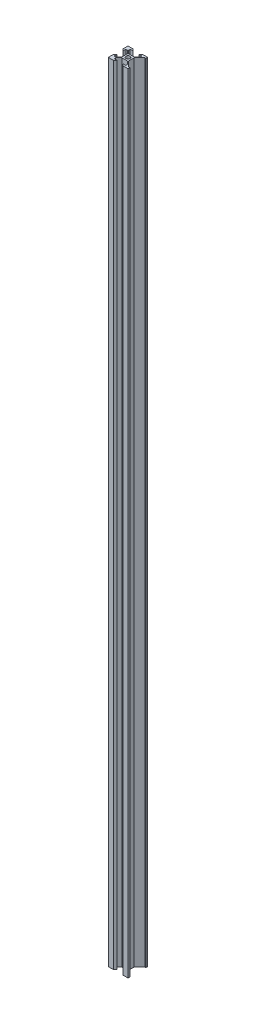
SolidWorks part; units mm, degrees
ref_plane "前视基准面" through (0, 0, 0) normal (0, 0, 1) x (1, 0, 0)
ref_plane "上视基准面" through (0, 0, 0) normal (0, 1, 0) x (1, 0, 0)
ref_plane "右视基准面" through (0, 0, 0) normal (1, 0, 0) x (0, 0, -1)
sketch "草图1" plane through (0, 0, 0) normal (0, 1, 0) x (1, 0, 0)
  line L0 (-25.721, 0) -> (73.7722, 0)
  line L1 (0, 21.255) -> (0, -16.6235)
  line L2 (-10, 21.255) -> (-10, -16.6235)
  line L3 (-25.721, 10) -> (73.7722, 10)
  line L4 (-4.9, 10) -> (-3.1, 8.2)
  line L5 (-3.1, 8.2) -> (-5.9236, 8.2)
  line L6 (-5.9236, 8.2) -> (-5.9236, 6.56)
  line L7 (-5.9236, 6.56) -> (-2.84, 3.4764)
  line L8 (-2.84, 3.4764) -> (2.84, 3.4764)
  line L9 (-10, 10) -> (0, 0) construction
  line L10 (5.9236, 6.56) -> (2.84, 3.4764)
  line L11 (5.9236, 8.2) -> (5.9236, 6.56)
  line L12 (3.1, 8.2) -> (5.9236, 8.2)
  line L13 (4.9, 10) -> (3.1, 8.2)
  line L14 (-10, -4.9) -> (-8.2, -3.1)
  line L15 (-8.2, -3.1) -> (-8.2, -5.9236)
  line L16 (-8.2, -5.9236) -> (-6.56, -5.9236)
  line L17 (-6.56, -5.9236) -> (-3.4764, -2.84)
  line L18 (-3.4764, 2.84) -> (-3.4764, -2.84)
  line L19 (-6.56, 5.9236) -> (-3.4764, 2.84)
  line L20 (-8.2, 5.9236) -> (-6.56, 5.9236)
  line L21 (-8.2, 3.1) -> (-8.2, 5.9236)
  line L22 (-10, 4.9) -> (-8.2, 3.1)
  line L23 (-25.721, -10) -> (73.7722, -10)
  line L24 (4.9, -10) -> (3.1, -8.2)
  line L25 (3.1, -8.2) -> (5.9236, -8.2)
  line L26 (5.9236, -8.2) -> (5.9236, -6.56)
  line L27 (5.9236, -6.56) -> (2.84, -3.4764)
  line L28 (-2.84, -3.4764) -> (2.84, -3.4764)
  line L29 (-5.9236, -6.56) -> (-2.84, -3.4764)
  line L30 (-5.9236, -8.2) -> (-5.9236, -6.56)
  line L31 (-3.1, -8.2) -> (-5.9236, -8.2)
  line L32 (-4.9, -10) -> (-3.1, -8.2)
  line L33 (50, 21.255) -> (50, -16.6235)
  line L34 (20, 21.255) -> (20, -16.6235)
  line L35 (10, 4.9) -> (8.2, 3.1)
  line L36 (8.2, 3.1) -> (8.2, 5.9236)
  line L37 (8.2, 5.9236) -> (6.56, 5.9236)
  line L38 (6.56, 5.9236) -> (3.4764, 2.84)
  line L39 (3.4764, 2.84) -> (3.4764, -2.84)
  line L40 (6.56, -5.9236) -> (3.4764, -2.84)
  line L41 (8.2, -5.9236) -> (6.56, -5.9236)
  line L42 (8.2, -3.1) -> (8.2, -5.9236)
  line L43 (10, -4.9) -> (8.2, -3.1)
  line L44 (15.1, 10) -> (16.9, 8.2)
  line L45 (16.9, 8.2) -> (14.0764, 8.2)
  line L46 (14.0764, 8.2) -> (14.0764, 6.56)
  line L47 (14.0764, 6.56) -> (17.16, 3.4764)
  line L48 (17.16, 3.4764) -> (22.84, 3.4764)
  line L49 (25.9236, 6.56) -> (22.84, 3.4764)
  line L50 (25.9236, 8.2) -> (25.9236, 6.56)
  line L51 (23.1, 8.2) -> (25.9236, 8.2)
  line L52 (24.9, 10) -> (23.1, 8.2)
  line L53 (10, -4.9) -> (11.8, -3.1)
  line L54 (11.8, -3.1) -> (11.8, -5.9236)
  line L55 (11.8, -5.9236) -> (13.44, -5.9236)
  line L56 (13.44, -5.9236) -> (16.5236, -2.84)
  line L57 (16.5236, 2.84) -> (16.5236, -2.84)
  line L58 (13.44, 5.9236) -> (16.5236, 2.84)
  line L59 (11.8, 5.9236) -> (13.44, 5.9236)
  line L60 (11.8, 3.1) -> (11.8, 5.9236)
  line L61 (10, 4.9) -> (11.8, 3.1)
  line L62 (24.9, -10) -> (23.1, -8.2)
  line L63 (23.1, -8.2) -> (25.9236, -8.2)
  line L64 (25.9236, -8.2) -> (25.9236, -6.56)
  line L65 (25.9236, -6.56) -> (22.84, -3.4764)
  line L66 (17.16, -3.4764) -> (22.84, -3.4764)
  line L67 (14.0764, -6.56) -> (17.16, -3.4764)
  line L68 (14.0764, -8.2) -> (14.0764, -6.56)
  line L69 (16.9, -8.2) -> (14.0764, -8.2)
  line L70 (15.1, -10) -> (16.9, -8.2)
  line L71 (30, 4.9) -> (28.2, 3.1)
  line L72 (28.2, 3.1) -> (28.2, 5.9236)
  line L73 (28.2, 5.9236) -> (26.56, 5.9236)
  line L74 (26.56, 5.9236) -> (23.4764, 2.84)
  line L75 (23.4764, 2.84) -> (23.4764, -2.84)
  line L76 (26.56, -5.9236) -> (23.4764, -2.84)
  line L77 (28.2, -5.9236) -> (26.56, -5.9236)
  line L78 (28.2, -3.1) -> (28.2, -5.9236)
  line L79 (30, -4.9) -> (28.2, -3.1)
  line L80 (6.56, 5.9236) -> (8.8364, 8.2)
  line L81 (35.1, 10) -> (36.9, 8.2)
  line L82 (36.9, 8.2) -> (34.0764, 8.2)
  line L83 (34.0764, 8.2) -> (34.0764, 6.56)
  line L84 (34.0764, 6.56) -> (37.16, 3.4764)
  line L85 (37.16, 3.4764) -> (42.84, 3.4764)
  line L86 (45.9236, 6.56) -> (42.84, 3.4764)
  line L87 (45.9236, 8.2) -> (45.9236, 6.56)
  line L88 (43.1, 8.2) -> (45.9236, 8.2)
  line L89 (44.9, 10) -> (43.1, 8.2)
  line L90 (30, -4.9) -> (31.8, -3.1)
  line L91 (31.8, -3.1) -> (31.8, -5.9236)
  line L92 (31.8, -5.9236) -> (33.44, -5.9236)
  line L93 (33.44, -5.9236) -> (36.5236, -2.84)
  line L94 (36.5236, 2.84) -> (36.5236, -2.84)
  line L95 (33.44, 5.9236) -> (36.5236, 2.84)
  line L96 (31.8, 5.9236) -> (33.44, 5.9236)
  line L97 (31.8, 3.1) -> (31.8, 5.9236)
  line L98 (30, 4.9) -> (31.8, 3.1)
  line L99 (44.9, -10) -> (43.1, -8.2)
  line L100 (43.1, -8.2) -> (45.9236, -8.2)
  line L101 (45.9236, -8.2) -> (45.9236, -6.56)
  line L102 (45.9236, -6.56) -> (42.84, -3.4764)
  line L103 (37.16, -3.4764) -> (42.84, -3.4764)
  line L104 (34.0764, -6.56) -> (37.16, -3.4764)
  line L105 (34.0764, -8.2) -> (34.0764, -6.56)
  line L106 (36.9, -8.2) -> (34.0764, -8.2)
  line L107 (35.1, -10) -> (36.9, -8.2)
  line L108 (50, 4.9) -> (48.2, 3.1)
  line L109 (48.2, 3.1) -> (48.2, 5.9236)
  line L110 (48.2, 5.9236) -> (46.56, 5.9236)
  line L111 (46.56, 5.9236) -> (43.4764, 2.84)
  line L112 (43.4764, 2.84) -> (43.4764, -2.84)
  line L113 (46.56, -5.9236) -> (43.4764, -2.84)
  line L114 (48.2, -5.9236) -> (46.56, -5.9236)
  line L115 (48.2, -3.1) -> (48.2, -5.9236)
  line L116 (50, -4.9) -> (48.2, -3.1)
  line L117 (13.44, 5.9236) -> (11.1636, 8.2)
  line L118 (30, 10) -> (40, 0) construction
  line L119 (10, 10) -> (20, 0) construction
  line L120 (8.8364, 8.2) -> (11.1636, 8.2)
  line L121 (8.8364, -8.2) -> (11.1636, -8.2)
  line L122 (6.56, -5.9236) -> (8.8364, -8.2)
  line L123 (13.44, -5.9236) -> (11.1636, -8.2)
  line L124 (26.56, 5.9236) -> (28.8364, 8.2)
  line L125 (28.8364, 8.2) -> (31.1636, 8.2)
  line L126 (33.44, 5.9236) -> (31.1636, 8.2)
  line L127 (26.56, -5.9236) -> (28.8364, -8.2)
  line L128 (28.8364, -8.2) -> (31.1636, -8.2)
  line L129 (33.44, -5.9236) -> (31.1636, -8.2)
  circle A0 centre (0, 0) radius 2.1
  circle A1 centre (20, 0) radius 2.1
  circle A2 centre (40, 0) radius 2.1
  circle A3 centre (20, 0) radius 2.1
  circle A4 centre (40, 0) radius 2.1
  point P22 (0, 3.4764)
  point P37 (-3.4764, 0)
  point P50 (0, -3.4764)
  point P65 (3.4764, 0)
  point P77 (20, 3.4764)
  point P92 (16.5236, 0)
  point P103 (20, -3.4764)
  point P114 (23.4764, 0)
  point P124 (40, 3.4764)
  point P139 (36.5236, 0)
  point P150 (40, -3.4764)
  point P161 (43.4764, 0)
  dimension "D1" = 3
  dimension "D2" = 4.2
  dimension "D3" = 20
  dimension "D6" = 1.8
  dimension "D7" = 1.64
  dimension "D8" = 2.84
  dimension "D9" = 3.1
  dimension "D10" = 45
  dimension "D11" = 0.9
  dimension "D16" = 2
  dimension "D4" = 10
  dimension "D5" = 10
  dimension "D12" = 10
  dimension "D13" = 60
  dimension "D14" = 30
  dimension "D15" = 3
extrude "凸台-拉伸1" add sketch "草图1" along normal blind 800 contours A0 L1 L8 L7 L6 L5 L4 L3 L2 L22 L21 L20 L19 L18 L0 | A0 L0 L18 L17 L16 L15 L14 L2 L23 L32 L31 L30 L29 L28 L1 | A1 L0 L57 L56 L123 L121 L122 L40 L39 A0 L1 L28 L27 L26 L25 L24 L23 L70 L69 L68 L67 L66 L34 | A1 L34 L48 L47 L46 L45 L44 L3 L13 L12 L11 L10 L8 L1 A0 L0 L39 L38 L80 L120 L117 L58 L57 | A2 L0 L112 L111 L110 L109 L108 L33 L3 L89 L88 L87 L86 L85 L84 L83 L82 L81 L52 L51 L50 L49 L48 L34 A1 L75 L74 L124 L125 L126 L95 L94 | A2 L0 L94 L93 L129 L128 L127 L76 L75 A1 L34 L66 L65 L64 L63 L62 L23 L107 L106 L105 L104 L103 L102 L101 L100 L99 L33 L116 L115 L114 L113 L112
sketch "草图2" plane through (0, 800, 0) normal (0, 1, 0) x (1, 0, 0)
  line L0 (4.9, 10) -> (15.1, 10) construction
  line L1 (10, 10) -> (54.3529, 10)
  line L2 (10, 10) -> (10, -16.4474)
  line L3 (10, -16.4474) -> (54.3529, -16.4474)
  line L4 (54.3529, 10) -> (54.3529, -16.4474)
extrude "切除-拉伸1" cut sketch "草图2" against normal through all both and the other way through all
